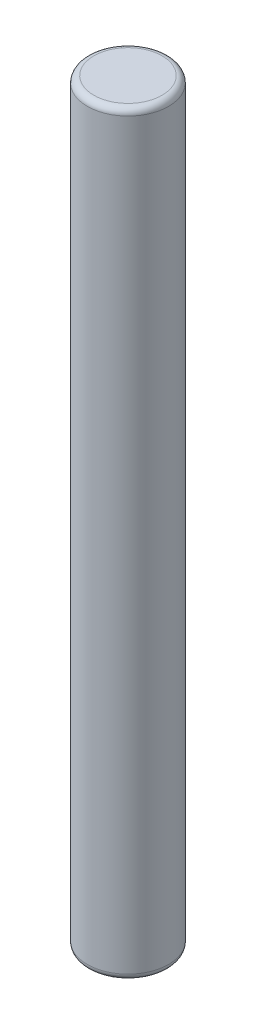
SolidWorks part; units mm, degrees
material "Plain Carbon Steel"
ref_plane "Front Plane" through (0, 0, 0) normal (0, 0, 1) x (1, 0, 0)
ref_plane "Top Plane" through (0, 0, 0) normal (0, 1, 0) x (1, 0, 0)
ref_plane "Right Plane" through (0, 0, 0) normal (1, 0, 0) x (0, 0, -1)
sketch "Sketch1" plane through (0, 0, 0) normal (0, 1, 0) x (1, 0, 0)
  circle A0 centre (0, 0) radius 4
  dimension "D1" = 8
extrude "Boss-Extrude1" add sketch "Sketch1" along normal blind 74.5
fillet "Fillet1" radius 0.635 2 edges at (0, 74.5, 4) (0, 0, 4)
